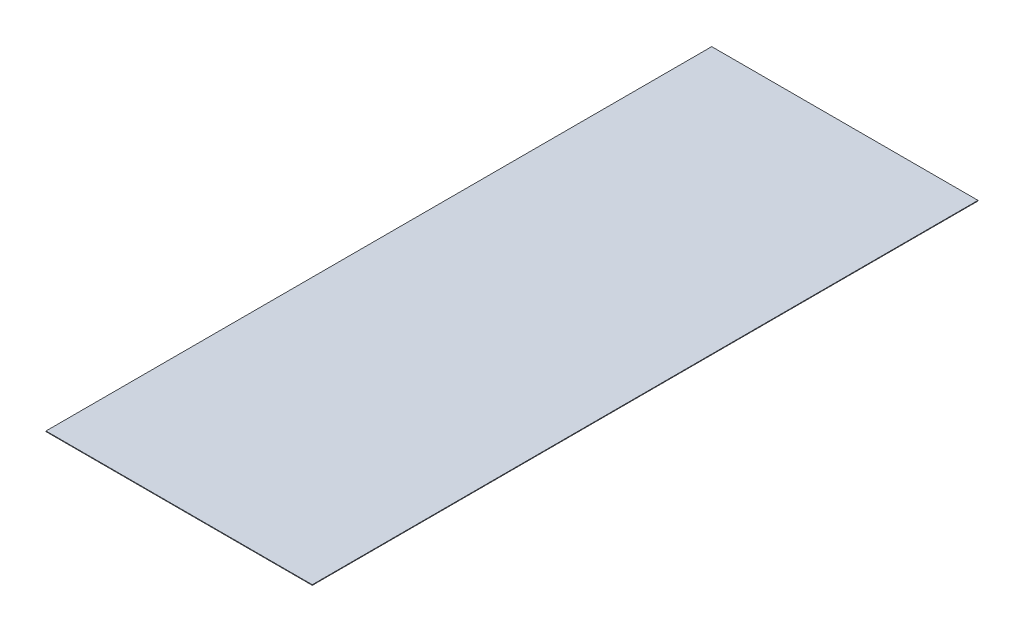
SolidWorks part; units mm, degrees
material "ASTM A36 Acero"
ref_plane "Alzado" through (0, 0, 0) normal (0, 0, 1) x (1, 0, 0)
ref_plane "Planta" through (0, 0, 0) normal (0, 1, 0) x (1, 0, 0)
ref_plane "Vista lateral" through (0, 0, 0) normal (1, 0, 0) x (0, 0, -1)
sketch "Croquis1" plane through (0, 0, 0) normal (0, 1, 0) x (1, 0, 0)
  line L1 (-609.6, -1524) -> (609.6, -1524)
  line L2 (-609.6, -1524) -> (-609.6, 1524)
  line L3 (-609.6, 1524) -> (609.6, 1524)
  line L4 (609.6, -1524) -> (609.6, 1524)
  line L5 (-609.6, -1524) -> (609.6, 1524) construction
  line L6 (-609.6, 1524) -> (609.6, -1524) construction
  point P0 (0, 0)
  dimension "D1" = 3048
  dimension "D2" = 1219.2
extrude "Saliente-Extruir1" add sketch "Croquis1" along normal blind 2.7
